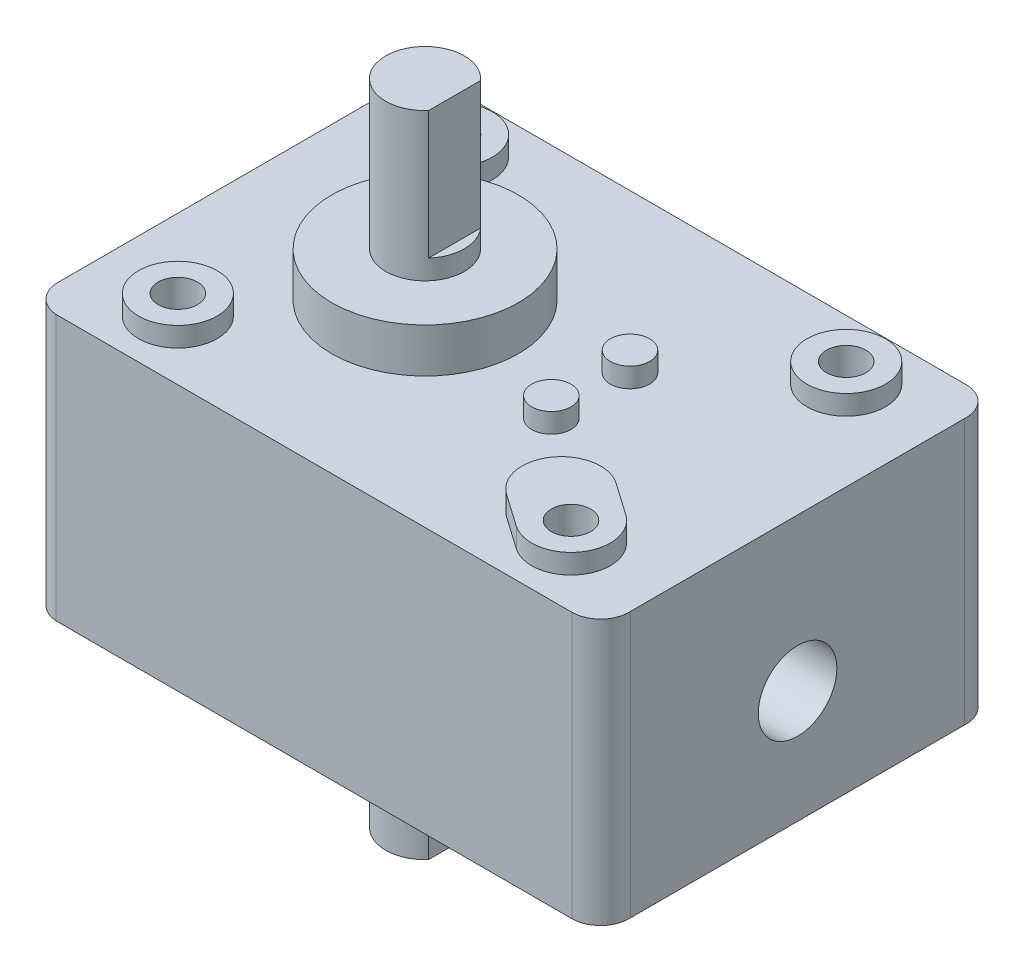
SolidWorks part; units mm, degrees
material "Zinc AG40A (Zn-4Al-0.4Mg; Zamak 3), fundido"
ref_plane "Alzado" through (0, 0, 0) normal (0, 0, 1) x (1, 0, 0)
ref_plane "Planta" through (0, 0, 0) normal (0, 1, 0) x (1, 0, 0)
ref_plane "Vista lateral" through (0, 0, 0) normal (1, 0, 0) x (0, 0, -1)
sketch "Croquis2" plane through (0, 0, 0) normal (0, 1, 0) x (1, 0, 0)
  line L0 (-29.06, 20.055) -> (29.05, -20.055) construction
  line L5 (-26.3205, 20.055) -> (26.15, 20.055)
  line L6 (-29.06, 17.15) -> (-29.06, -17.15)
  line L7 (-26.3205, -20.055) -> (26.15, -20.055)
  line L8 (29.05, 16.9796) -> (29.05, -16.9796)
  line L9 (-26.15, 17.15) -> (26.15, 17.15) construction
  line L10 (-26.15, 17.15) -> (-26.15, -17.15) construction
  line L11 (-26.15, -17.15) -> (26.15, -17.15) construction
  line L12 (26.15, 17.15) -> (26.15, -17.15) construction
  line L13 (-26.15, 17.15) -> (26.15, -17.15) construction
  line L14 (-26.15, -17.15) -> (26.15, 17.15) construction
  line L15 (29.05, 20.055) -> (-29.06, -20.055) construction
  arc A0 (-26.3205, 20.055) -> (-29.06, 17.15) centre (-26.15, 17.15) ccw
  arc A1 (29.05, 16.9796) -> (26.15, 20.055) centre (26.15, 17.15) ccw
  arc A3 (-29.06, -17.15) -> (-26.3205, -20.055) centre (-26.15, -17.15) ccw
  arc A4 (26.15, -20.055) -> (29.05, -16.9796) centre (26.15, -17.15) ccw
  point P0 (0, 0)
  point P6 (0, 0)
  dimension "D5" = 5.82
  dimension "D1" = 58.11
  dimension "D2" = 40.11
  dimension "D3" = 52.3
  dimension "D4" = 34.3
extrude "Saliente-Extruir1" add sketch "Croquis2" along normal blind 27
sketch "Croquis3" plane through (0, 27, 0) normal (0, 1, 0) x (1, 0, 0)
  line L0 (20, -14) -> (16.7231, -11.7062)
  line L1 (-20, 14) -> (20, 14) construction
  line L2 (-20, 14) -> (-20, -14) construction
  line L3 (-20, -14) -> (20, -14) construction
  line L4 (20, 14) -> (20, -14) construction
  line L5 (-20, 14) -> (20, -14) construction
  line L6 (-20, -14) -> (20, 14) construction
  line L7 (19.0169, -8.4292) -> (22.2938, -10.7231)
  line L8 (14.4292, -14.9831) -> (17.7062, -17.2769)
  line L11 (8, 4) -> (8, -4) construction
  circle A1 centre (-20, 14) radius 4
  circle A2 centre (20, 14) radius 4
  arc A3 (17.7062, -17.2769) -> (22.2938, -10.7231) centre (20, -14) ccw
  circle A4 centre (-20, -14) radius 4
  arc A5 (19.0169, -8.4292) -> (14.4292, -14.9831) centre (16.7231, -11.7062) ccw
  circle A7 centre (8, 4) radius 2
  circle A8 centre (8, -4) radius 2
  point P0 (0, 0)
  point P21 (8, 0)
  point P25 (8, 0)
  dimension "D3" = 8
  dimension "D4" = 8
  dimension "D5" = 8
  dimension "D6" = 8
  dimension "D8" = 8
  dimension "D13" = 4
  dimension "D14" = 4
  dimension "D1" = 40
  dimension "D2" = 28
  dimension "D7" = 4
  dimension "D9" = 8
  dimension "D12" = 8
extrude "Saliente-Extruir2" add sketch "Croquis3" along normal blind 2
sketch "Croquis6" plane through (0, 29, 0) normal (0, 1, 0) x (1, 0, 0)
  circle A0 centre (-20, 14) radius 2
  circle A1 centre (20, 14) radius 2
  circle A2 centre (20, -14) radius 2
  circle A3 centre (-20, -14) radius 2
  dimension "D1" = 4
  dimension "D2" = 4
  dimension "D3" = 4
  dimension "D4" = 4
extrude "Cortar-Extruir2" cut sketch "Croquis6" against normal blind 10
sketch "Croquis9" plane through (0, 0, 0) normal (0, -1, 0) x (1, 0, 0)
  line L0 (14.2551, 14.8612) -> (17.5353, 17.1504)
  line L1 (-20, 14) -> (20, 14) construction
  line L2 (-20, 14) -> (-20, -14) construction
  line L3 (-20, -14) -> (20, -14) construction
  line L4 (20, 14) -> (20, -14) construction
  line L5 (-20, 14) -> (20, -14) construction
  line L6 (-20, -14) -> (20, 14) construction
  line L9 (8, 4) -> (8, -4) construction
  line L10 (22.2938, 10.7231) -> (18.8382, 8.3041)
  circle A0 centre (-20, 14) radius 4
  circle A3 centre (-20, -14) radius 4
  circle A5 centre (8, 4) radius 2
  circle A6 centre (8, -4) radius 2
  circle A7 centre (20, -14) radius 4
  arc A8 (14.2551, 14.8612) -> (18.8382, 8.3041) centre (16.5444, 11.5811) ccw
  arc A10 (22.2938, 10.7231) -> (17.5353, 17.1504) centre (20, 14) ccw
  point P0 (0, 0)
  point P13 (8, 0)
  point P17 (8, 0)
  dimension "D3" = 8
  dimension "D4" = 4
  dimension "D5" = 8
  dimension "D6" = 8
  dimension "D7" = 4
  dimension "D9" = 4
  dimension "D10" = 4
  dimension "D11" = 4
  dimension "D1" = 40
  dimension "D2" = 28
  dimension "D8" = 8
  dimension "D12" = 8
extrude "Saliente-Extruir4" add sketch "Croquis9" along normal blind 2
sketch "Croquis10" plane through (0, -2, 0) normal (0, -1, 0) x (1, 0, 0)
  circle A0 centre (20, -14) radius 2
  circle A1 centre (20, 14) radius 2
  circle A2 centre (-20, 14) radius 2
  circle A3 centre (-20, -14) radius 2
  dimension "D1" = 4
  dimension "D2" = 4
  dimension "D3" = 4
  dimension "D4" = 4
extrude "Cortar-Extruir3" cut sketch "Croquis10" against normal blind 10
sketch "Croquis11" plane through (0, 27, 0) normal (0, 1, 0) x (1, 0, 0)
  line L0 (29.05, -0.6488) -> (-8.85, 0) construction
  line L1 (29.05, -16.9796) -> (29.05, 16.9796) construction
  circle A0 centre (-8.85, 0) radius 9.5
  dimension "D2" = 19
  dimension "D1" = 37.9
extrude "Saliente-Extruir5" add sketch "Croquis11" along normal blind 4.5
sketch "Croquis12" plane through (0, 0, 0) normal (0, -1, 0) x (1, 0, 0)
  line L0 (29.05, 0) -> (-8.85, 0) construction
  line L2 (29.05, 16.9796) -> (29.05, -16.9796) construction
  circle A0 centre (-8.85, 0) radius 9.5
  dimension "D2" = 19
  dimension "D1" = 37.9
extrude "Saliente-Extruir6" add sketch "Croquis12" along normal blind 4.5
sketch "Croquis13" plane through (0, 31.5, 0) normal (0, 1, 0) x (1, 0, 0)
  circle A0 centre (-8.85, 0) radius 4
  dimension "D1" = 8
extrude "Saliente-Extruir7" add sketch "Croquis13" along normal blind 15
sketch "Croquis15" plane through (0, 46.5, 0) normal (0, 1, 0) x (1, 0, 0)
  line L0 (-12.85, 0) -> (-5.85, 0) construction
  line L1 (-5.85, 2.6458) -> (-5.85, -2.6458)
  arc A0 (-5.85, -2.6458) -> (-5.85, 2.6458) centre (-8.85, 0) ccw
  point P9 (-5.85, 0)
  dimension "D1" = 7
extrude "Cortar-Extruir6" cut sketch "Croquis15" against normal blind 13
sketch "Croquis16" plane through (0, -4.5, 0) normal (0, -1, 0) x (1, 0, 0)
  circle A0 centre (-8.85, 0) radius 4
  dimension "D1" = 8
extrude "Saliente-Extruir8" add sketch "Croquis16" along normal blind 15
sketch "Croquis17" plane through (0, -19.5, 0) normal (0, -1, 0) x (1, 0, 0)
  line L0 (-12.85, 0) -> (-5.85, 0) construction
  line L1 (-5.85, 2.6458) -> (-5.85, -2.6458)
  arc A0 (-5.85, -2.6458) -> (-5.85, 2.6458) centre (-8.85, 0) ccw
  point P9 (-5.85, 0)
  dimension "D1" = 7
extrude "Cortar-Extruir7" cut sketch "Croquis17" against normal blind 13
sketch "Croquis18" plane through (29.05, 0, 0) normal (1, 0, 0) x (0, 0, -1)
  line L0 (0, 27) -> (0, 11.5) construction
  line L2 (-16.9796, 27) -> (16.9796, 27) construction
  circle A0 centre (0, 11.5) radius 4
  dimension "D2" = 8
  dimension "D1" = 15.5
extrude "Cortar-Extruir8" cut sketch "Croquis18" against normal blind 20
